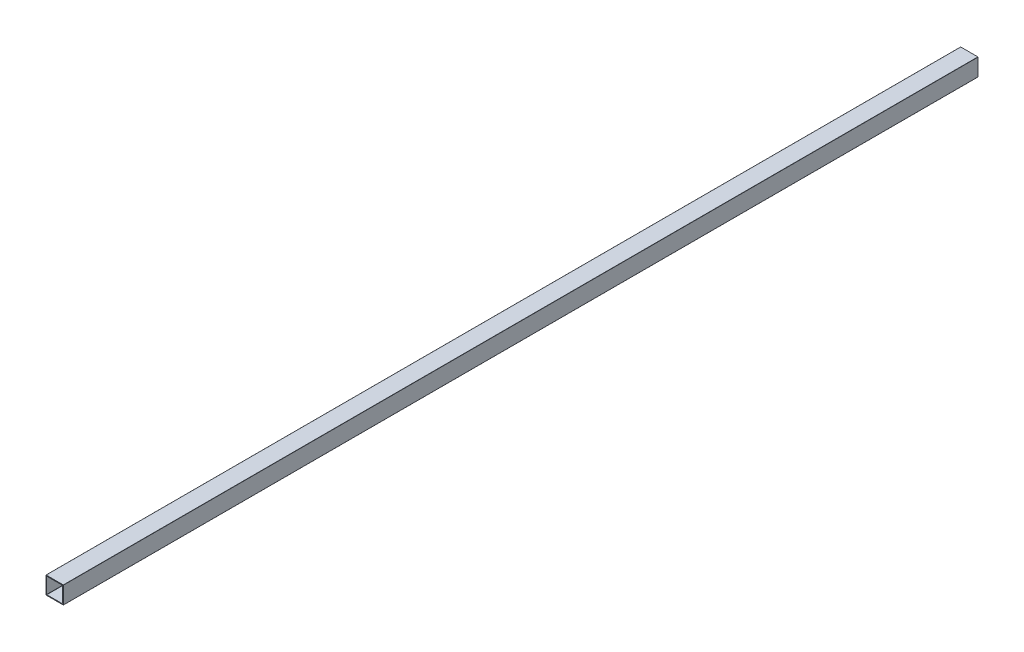
SolidWorks part; units mm, degrees
material "AISI 1035 Acero (SS)"
ref_plane "Alzado" through (0, 0, 0) normal (0, 0, 1) x (1, 0, 0)
ref_plane "Planta" through (0, 0, 0) normal (0, 1, 0) x (1, 0, 0)
ref_plane "Vista lateral" through (0, 0, 0) normal (1, 0, 0) x (0, 0, -1)
sketch "Croquis1" plane through (0, 0, 0) normal (0, 0, 1) x (1, 0, 0)
  line L0 (-52.6, -52.6) -> (-52.6, 52.6)
  line L1 (-57.15, -57.15) -> (57.15, -57.15)
  line L2 (-57.15, -57.15) -> (-57.15, 57.15)
  line L3 (-57.15, 57.15) -> (57.15, 57.15)
  line L4 (57.15, -57.15) -> (57.15, 57.15)
  line L5 (-57.15, -57.15) -> (57.15, 57.15) construction
  line L6 (-57.15, 57.15) -> (57.15, -57.15) construction
  line L7 (-52.6, 52.6) -> (52.6, 52.6)
  line L8 (52.6, -52.6) -> (52.6, 52.6)
  line L9 (-52.6, -52.6) -> (52.6, -52.6)
  point P0 (0, 0)
  dimension "D2" = 114.3
  dimension "D3" = 4.55
extrude "Saliente-Extruir1" add sketch "Croquis1" against normal blind 6000
fillet "Redondeo1" radius 1 8 edges at (-52.6, 52.6, -3000) (52.6, 52.6, -3000) (52.6, -52.6, -3000) (-57.15, -57.15, -3000) (-57.15, 57.15, -3000) (-52.6, -52.6, -3000) (57.15, -57.15, -3000) (57.15, 57.15, -3000)
